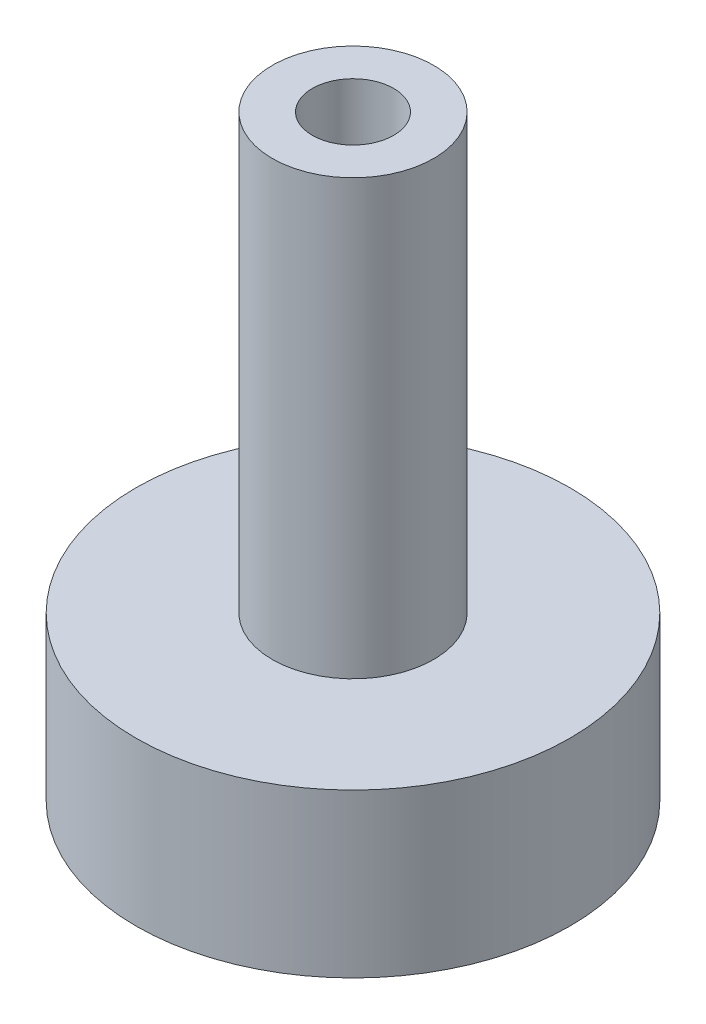
SolidWorks part; units mm, degrees
ref_plane "Front Plane" through (0, 0, 0) normal (0, 0, 1) x (1, 0, 0)
ref_plane "Top Plane" through (0, 0, 0) normal (0, 1, 0) x (1, 0, 0)
ref_plane "Right Plane" through (0, 0, 0) normal (1, 0, 0) x (0, 0, -1)
sketch "Sketch1" plane through (0, 0, 0) normal (0, 1, 0) x (1, 0, 0)
  circle A0 centre (-27.9181, -5.991) radius 2.3622 construction
  circle A1 centre (-27.9181, -5.991) radius 6.35
extrude "Boss-Extrude1" add sketch "Sketch1" along normal blind 4.7625
sketch "Sketch4" plane through (0, 0, 0) normal (0, 1, 0) x (1, 0, 0)
  circle A0 centre (-27.9181, -5.991) radius 2.3622
  circle A1 centre (-27.9181, -5.991) radius 1.1906
extrude "Boss-Extrude2" add sketch "Sketch4" along normal blind 17.4625
